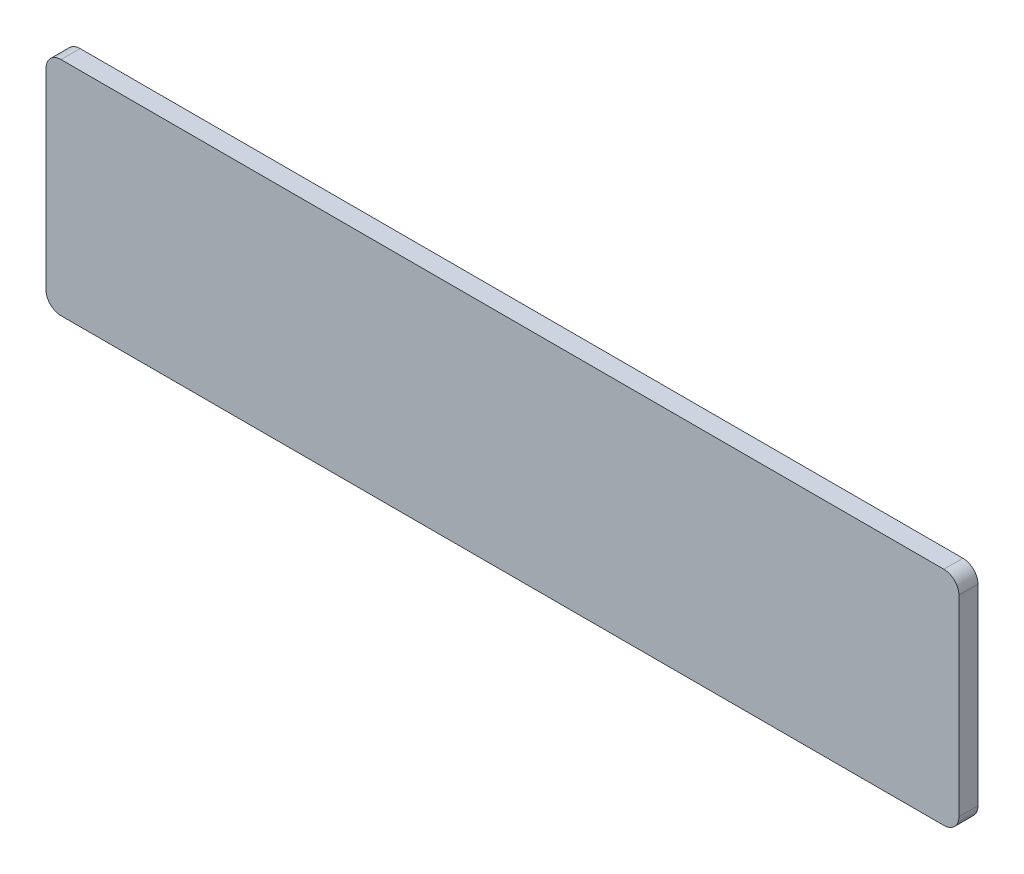
SolidWorks part; units mm, degrees
ref_plane "Front Plane" through (0, 0, 0) normal (0, 0, 1) x (1, 0, 0)
ref_plane "Top Plane" through (0, 0, 0) normal (0, 1, 0) x (1, 0, 0)
ref_plane "Right Plane" through (0, 0, 0) normal (1, 0, 0) x (0, 0, -1)
sketch "Sketch2" plane through (0, 0, 0) normal (0, 0, 1) x (1, 0, 0)
  line L1 (0, 0) -> (-607.57, 0)
  line L2 (0, 0) -> (0, 147.67)
  line L3 (0, 147.67) -> (-607.57, 147.67)
  line L4 (-607.57, 0) -> (-607.57, 147.67)
  dimension "D1" = 147.67
  dimension "607.57mm" = 607.57
extrude "Boss-Extrude1" add sketch "Sketch2" along normal blind 12.7
fillet "Fillet1" radius 10 4 edges at (0, 0, 6.35) (-607.57, 0, 6.35) (-607.57, 147.67, 6.35) (0, 147.67, 6.35)
